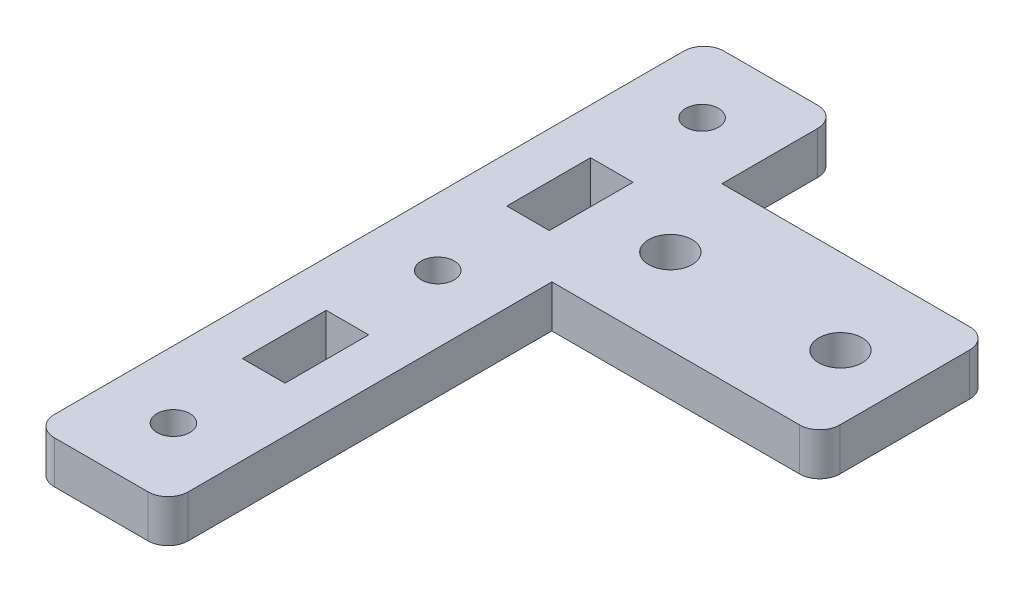
SolidWorks part; units mm, degrees
ref_plane "Front Plane" through (0, 0, 0) normal (0, 0, 1) x (1, 0, 0)
ref_plane "Top Plane" through (0, 0, 0) normal (0, 1, 0) x (1, 0, 0)
ref_plane "Right Plane" through (0, 0, 0) normal (1, 0, 0) x (0, 0, -1)
sketch "Sketch1" plane through (0, 0, 0) normal (0, 1, 0) x (1, 0, 0)
  line L0 (60, 70) -> (0, 70) construction
  line L1 (0, 0) -> (20, 0)
  line L2 (0, 0) -> (0, 100)
  line L3 (0, 100) -> (20, 100)
  line L4 (20, 0) -> (20, 57.3)
  line L5 (20, 82.7) -> (60, 82.7)
  line L7 (20, 57.3) -> (60, 57.3)
  line L8 (60, 82.7) -> (60, 57.3)
  line L9 (20, 82.7) -> (20, 100)
  dimension "D1" = 100
  dimension "D2" = 20
  dimension "D3" = 25.4
  dimension "D4" = 40
  dimension "D5" = 30
extrude "Boss-Extrude1" add sketch "Sketch1" along normal blind 6.35
sketch "Sketch2" plane through (0, 6.35, 0) normal (0, 1, 0) x (1, 0, 0)
  line L0 (10, 100) -> (10, 0) construction
  line L1 (20, 100) -> (0, 100) construction
  line L2 (0, 0) -> (20, 0) construction
  line L3 (60, 70) -> (0, 70) construction
  line L4 (6.825, 76.25) -> (13.175, 76.25)
  line L5 (6.825, 76.25) -> (6.825, 63.75)
  line L6 (6.825, 63.75) -> (13.175, 63.75)
  line L7 (13.175, 76.25) -> (13.175, 63.75)
  line L8 (6.825, 36.7758) -> (13.175, 36.7758)
  line L9 (6.825, 36.7758) -> (6.825, 24.2758)
  line L10 (6.825, 24.2758) -> (13.175, 24.2758)
  line L11 (13.175, 36.7758) -> (13.175, 24.2758)
  line L18 (60, 57.3) -> (60, 82.7) construction
  line L19 (0, 100) -> (0, 0) construction
  point P24 (6.825, 30.5258)
  point P26 (6.825, 70)
  point P27 (10, 24.2758)
  dimension "D1" = 12.5
  dimension "D2" = 6.35
  dimension "D3" = 6.35
  dimension "D4" = 39.4742
extrude "Cut-Extrude1" cut sketch "Sketch2" against normal through all
hole_wizard "#10 (0.1935) Diameter Hole2" positions "Sketch6" profile "Sketch5" hole size "#10" standard "ANSI Inch" end condition through all
sketch "Sketch6" plane through (0, 6.35, 0) normal (0, 1, 0) x (1, 0, 0)
  line L0 (10, 100) -> (10, 0) construction
  line L1 (20, 100) -> (0, 100) construction
  line L2 (0, 0) -> (20, 0) construction
  line L8 (6.825, 76.25) -> (6.825, 63.75) construction
  line L9 (6.825, 36.7758) -> (6.825, 24.2758) construction
  point P0 (10, 89.7371)
  point P2 (10, 50.2629)
  point P4 (10, 10.7887)
  point P31 (6.825, 70)
  point P34 (6.825, 70)
  point P37 (6.825, 30.5258)
  dimension "D1" = 19.7371
  dimension "D2" = 19.7371
  dimension "D3" = 19.7371
sketch "Sketch5" plane through (10, 6.35, -89.7371) normal (1, 0, 0) x (0, 0, 1)
  line L0 (0, 0) -> (0, 6.35)
  line L1 (0, 6.35) -> (2.4574, 6.35)
  line L2 (2.4574, 6.35) -> (2.4574, 0)
  line L5 (2.4574, 0) -> (0, 0)
  line L11 (0, -6.35) -> (0, 107.95) construction
  dimension "Thru Hole Dia." = 4.9149
  dimension "Thru Hole Depth" = 6.35
sketch "Sketch7" plane through (0, 6.35, 0) normal (0, 1, 0) x (1, 0, 0)
  line L0 (60, 70) -> (0, 70) construction
  line L1 (60, 57.3) -> (60, 82.7) construction
  line L2 (0, 100) -> (0, 0) construction
  circle A0 centre (25, 70) radius 3.2436
  circle A1 centre (50.4, 70) radius 3.2436
  dimension "D1" = 6.4872
  dimension "D2" = 25.4
  dimension "D3" = 25
extrude "Cut-Extrude2" cut sketch "Sketch7" against normal through all
fillet "Fillet1" radius 3 6 edges at (0, 3.175, 0) (20, 3.175, 0) (60, 3.175, -57.3) (60, 3.175, -82.7) (20, 3.175, -100) (0, 3.175, -100)
